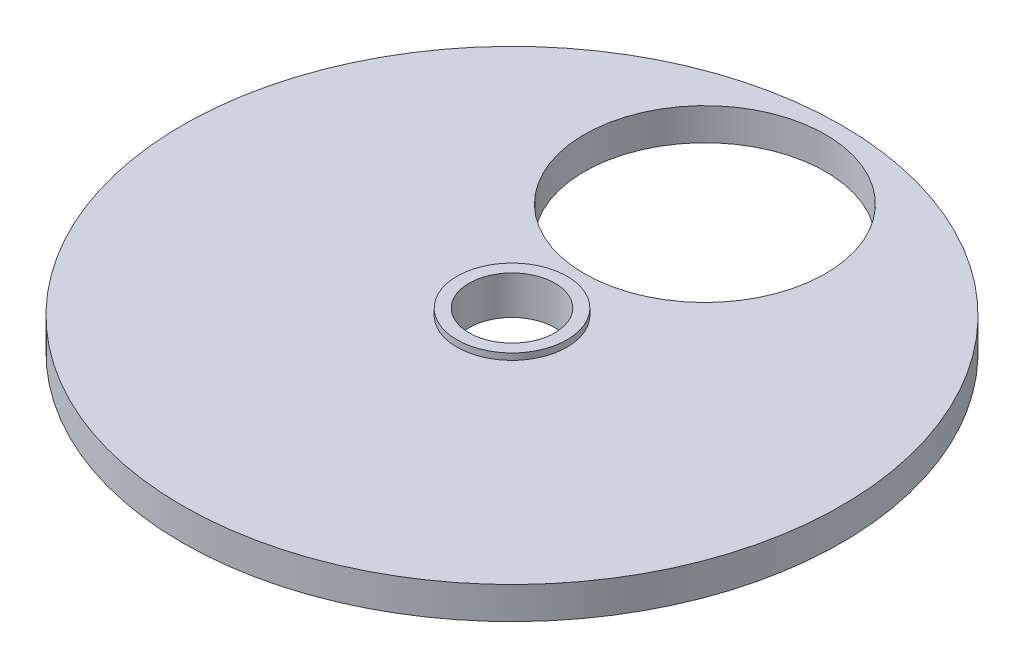
SolidWorks part; units mm, degrees
ref_plane "Front Plane" through (0, 0, 0) normal (0, 0, 1) x (1, 0, 0)
ref_plane "Top Plane" through (0, 0, 0) normal (0, 1, 0) x (1, 0, 0)
ref_plane "Right Plane" through (0, 0, 0) normal (1, 0, 0) x (0, 0, -1)
sketch "Sketch1" plane through (0, 0, 0) normal (0, 1, 0) x (1, 0, 0)
  circle A0 centre (0, 0) radius 20.5
  dimension "D1" = 41
extrude "Boss-Extrude1" add sketch "Sketch1" along normal blind 2
sketch "Sketch2" plane through (0, 2, 0) normal (0, 1, 0) x (1, 0, 0)
  circle A0 centre (0, 0) radius 2.675
  dimension "D1" = 5.35
extrude "Cut-Extrude1" cut sketch "Sketch2" against normal blind 2
sketch "Sketch3" plane through (0, 2, 0) normal (0, 1, 0) x (1, 0, 0)
  circle A0 centre (0, 0) radius 3.425
  circle A1 centre (0, 0) radius 2.675
  dimension "D1" = 5.35
  dimension "D2" = 6.85
extrude "Boss-Extrude2" add sketch "Sketch3" along normal blind 0.4
sketch "Sketch5" plane through (0, 2, 0) normal (0, 1, 0) x (1, 0, 0)
  circle A0 centre (0, 12) radius 7.5
  point P4 (0, 0)
  point P6 (0, 0)
  dimension "D1" = 15
  dimension "D2" = 12
extrude "Cut-Extrude3" cut sketch "Sketch5" against normal blind 2
